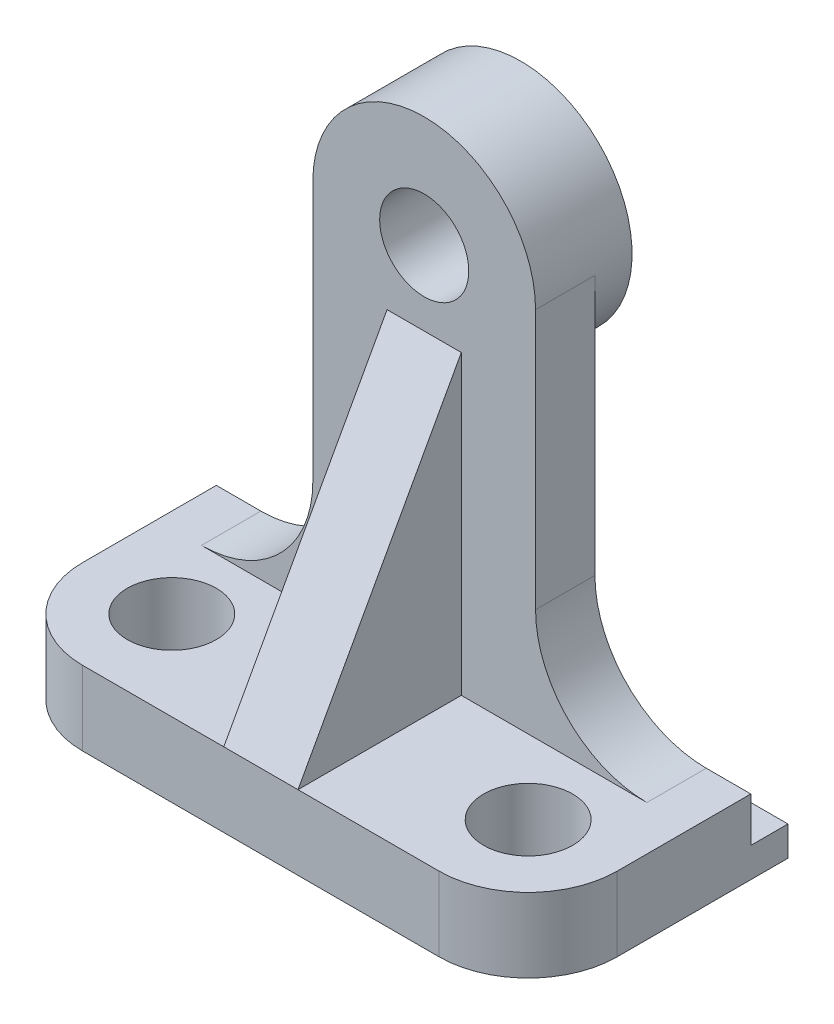
SolidWorks part; units mm, degrees
ref_plane "Front Plane" through (0, 0, 0) normal (0, 0, 1) x (1, 0, 0)
ref_plane "Top Plane" through (0, 0, 0) normal (0, 1, 0) x (1, 0, 0)
ref_plane "Right Plane" through (0, 0, 0) normal (1, 0, 0) x (0, 0, -1)
sketch "Sketch1" plane through (0, 0, 0) normal (0, 1, 0) x (1, 0, 0)
  line L1 (-36, 17.5) -> (36, 17.5)
  line L2 (36, 17.5) -> (36, -5.5)
  line L3 (24, -17.5) -> (-24, -17.5)
  line L5 (-36, 17.5) -> (-36, -5.5)
  arc A0 (36, -5.5) -> (24, -17.5) centre (24, -5.5) cw
  circle A1 centre (24, -5.5) radius 6
  circle A2 centre (-24, -5.5) radius 6
  arc A3 (-36, -5.5) -> (-24, -17.5) centre (-24, -5.5) ccw
  dimension "D1" = 12
  dimension "D2" = 12
  dimension "D5" = 17.5
  dimension "D6" = 17.5
  dimension "D3" = 36
  dimension "D4" = 36
extrude "Boss-Extrude1" add sketch "Sketch1" along normal blind 4
sketch "Sketch2" plane through (0, 4, 0) normal (0, 1, 0) x (1, 0, 0)
  line L1 (36, 12.5) -> (-36, 12.5)
  line L4 (36, -5.5) -> (36, 17.5)
  line L5 (36, 17.5) -> (-36, 17.5)
  line L6 (-36, 17.5) -> (-36, -5.5)
  line L7 (-24, -17.5) -> (24, -17.5)
  line L8 (36, -5.5) -> (36, 12.5)
  line L10 (-36, 12.5) -> (-36, -5.5)
  line L11 (-24, -17.5) -> (24, -17.5)
  line L13 (36, 17.5) -> (-36, 17.5)
  line L14 (36, -5.5) -> (36, 17.5)
  line L15 (-24, -17.5) -> (24, -17.5)
  line L16 (-36, 17.5) -> (-36, -5.5)
  line L18 (36, -5.5) -> (36, 12.5)
  line L19 (-24, -17.5) -> (24, -17.5)
  line L20 (-36, 12.5) -> (-36, -5.5)
  circle A1 centre (-24, -5.5) radius 6
  arc A2 (-36, -5.5) -> (-24, -17.5) centre (-24, -5.5) ccw
  arc A3 (24, -17.5) -> (36, -5.5) centre (24, -5.5) ccw
  arc A4 (-36, -5.5) -> (-24, -17.5) centre (-24, -5.5) ccw
  arc A5 (24, -17.5) -> (36, -5.5) centre (24, -5.5) ccw
  circle A6 centre (-24, -5.5) radius 6
  circle A7 centre (24, -5.5) radius 6
  circle A8 centre (24, -5.5) radius 6
  arc A10 (24, -17.5) -> (36, -5.5) centre (24, -5.5) ccw
  arc A11 (-36, -5.5) -> (-24, -17.5) centre (-24, -5.5) ccw
  arc A12 (24, -17.5) -> (36, -5.5) centre (24, -5.5) ccw
  arc A13 (-36, -5.5) -> (-24, -17.5) centre (-24, -5.5) ccw
  line M16 (36, -5.5) -> (36, 17.5)
  line M18 (-36, 17.5) -> (-36, -5.5)
  arc M19 (-36, -5.5) -> (-24, -17.5) centre (-24, -5.5) ccw
  line M20 (-24, -17.5) -> (24, -17.5)
  arc M21 (24, -17.5) -> (36, -5.5) centre (24, -5.5) ccw
  circle M22 centre (24, -5.5) radius 6
  circle M23 centre (-24, -5.5) radius 6
  dimension "D2" = 0
  dimension "D1" = 0
  dimension "D3" = 0
  dimension "D4" = 0
extrude "Boss-Extrude2" add sketch "Sketch2" along normal blind 6 contours L1 M16 M18 M19 M20 M21 M22 M23
ref_plane "Plane2" through (0, 0, -12.5) normal (0, 0, 1) x (1, 0, 0)
sketch "Sketch6" plane through (0, 0, -12.5) normal (0, 0, 1) x (1, 0, 0)
  line L2 (-24, 10) -> (24, 10) construction
  line L4 (15, 60) -> (15, 25)
  line L7 (-15, 60) -> (-15, 25)
  line L9 (-30, 10) -> (30, 10)
  arc A0 (15, 60) -> (-15, 60) centre (0, 60) ccw
  circle A1 centre (0, 60) radius 6
  arc A2 (15, 25) -> (30, 10) centre (30, 25) ccw
  arc A3 (-15, 25) -> (-30, 10) centre (-30, 25) cw
  point P21 (15, 10)
  point P24 (-15, 10)
  dimension "D1" = 15
  dimension "D2" = 12
  dimension "D3" = 60
extrude "Boss-Extrude3" add sketch "Sketch6" along normal blind 8
sketch "Sketch7" plane through (0, 0, -12.5) normal (0, 0, -1) x (-1, 0, 0)
  line L7 (-36, 4) -> (36, 4)
  line L8 (36, 4) -> (36, 10)
  line L9 (36, 10) -> (30, 10)
  line L10 (15, 25) -> (15, 60)
  line L11 (-15, 60) -> (-15, 25)
  line L12 (-30, 10) -> (-36, 10)
  line L13 (-36, 10) -> (-36, 4)
  circle A0 centre (0, 60) radius 6 construction
  circle A1 centre (0, 60) radius 6
  circle A2 centre (0, 60) radius 15
  arc A3 (15, 25) -> (30, 10) centre (30, 25) ccw
  arc A4 (15, 60) -> (-15, 60) centre (0, 60) ccw
  arc A5 (-30, 10) -> (-15, 25) centre (-30, 25) ccw
  arc A7 (15, 60) -> (-15, 60) centre (0, 60) ccw
  arc M17 (15, 60) -> (-15, 60) centre (0, 60) ccw
  circle M22 centre (0, 60) radius 6
  dimension "D1" = 0
extrude "Boss-Extrude4" add sketch "Sketch7" along normal blind 5 contours A2 M17 M22
sketch "Sketch8" plane through (0, 0, 0) normal (1, 0, 0) x (0, 0, -1)
  line L1 (-17.5, 10) -> (4.5, 50)
  line L2 (4.5, 25) -> (4.5, 60) construction
  dimension "D1" = 50
rib "Rib1" sketch "Sketch8" sketch "Sketch8" thickness 10 extrusion direction parallel to sketch draft on no parameters "D1"=10
